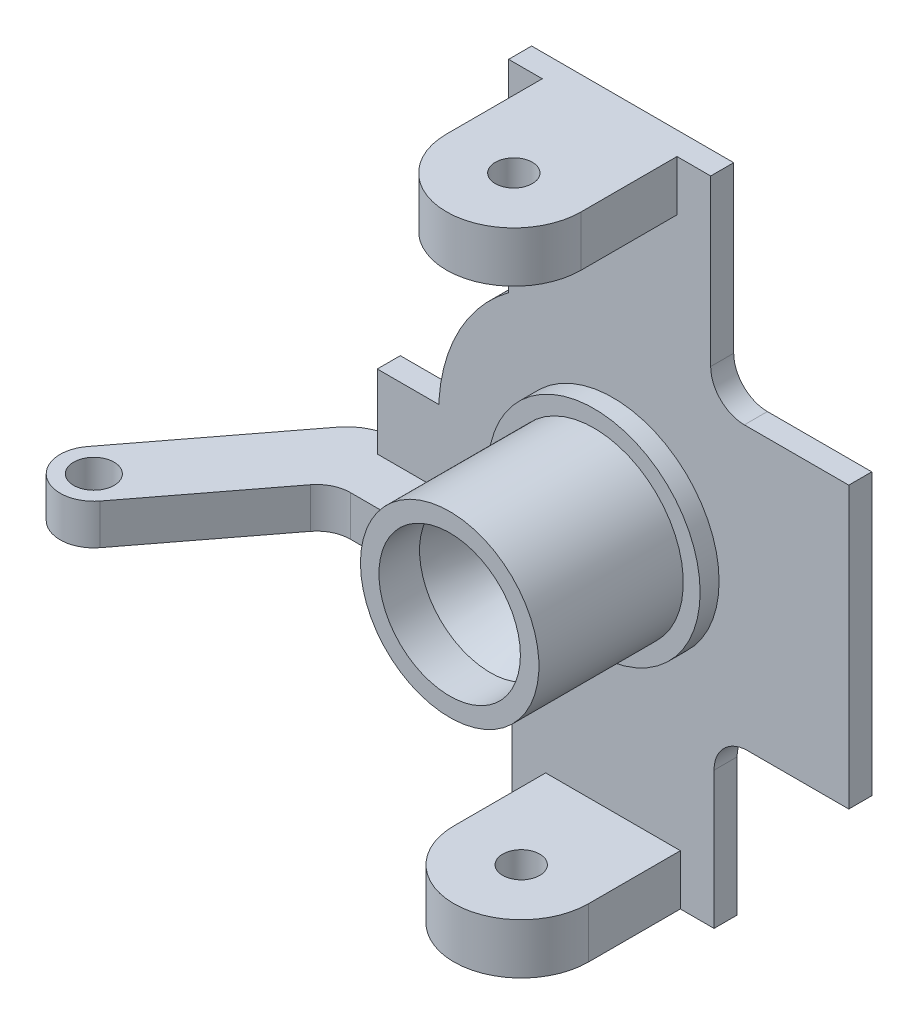
SolidWorks part; units mm, degrees
ref_plane "정면" through (0, 0, 0) normal (0, 0, 1) x (1, 0, 0)
ref_plane "윗면" through (0, 0, 0) normal (0, 1, 0) x (1, 0, 0)
ref_plane "우측면" through (0, 0, 0) normal (1, 0, 0) x (0, 0, -1)
sketch "스케치1" plane through (0, 0, 0) normal (0, 0, 1) x (1, 0, 0)
  line L0 (-34.9988, -181.1811) -> (-34.9988, -140.4811)
  line L1 (-95.9988, 11.8189) -> (-35.9988, 11.8189)
  line L2 (-134.9988, -87.3111) -> (-134.9988, -121.1811)
  line L3 (-94.9988, -181.1811) -> (-34.9988, -181.1811)
  line L4 (5.0012, -47.1811) -> (5.0012, -130.4811)
  line L5 (-24.9988, -130.4811) -> (5.0012, -130.4811)
  line L6 (-35.9988, 11.8189) -> (-35.9988, -37.1811)
  line L7 (-25.9988, -47.1811) -> (5.0012, -47.1811)
  line L8 (-134.9988, -121.1811) -> (-104.9988, -121.1811)
  line L9 (-94.9988, -131.1811) -> (-94.9988, -181.1811)
  line L11 (-95.9988, -48.1811) -> (-95.9988, 11.8189)
  line L12 (-134.9988, -87.3111) -> (-116.6823, -87.3111)
  line L13 (-116.6823, -87.3111) -> (-116.6823, -86.2066)
  arc A0 (-95.9988, -48.1811) -> (-116.6823, -86.2066) centre (-64.9988, -89.6811) ccw
  arc A1 (-35.9988, -37.1811) -> (-25.9988, -47.1811) centre (-25.9988, -37.1811) ccw
  arc A2 (-24.9988, -130.4811) -> (-34.9988, -140.4811) centre (-24.9988, -140.4811) ccw
  arc A3 (-94.9988, -131.1811) -> (-104.9988, -121.1811) centre (-104.9988, -131.1811) ccw
  point P17 (-35.9988, -47.1811)
  point P20 (-34.9988, -130.4811)
  point P23 (-94.9988, -121.1811)
  dimension "D8" = 10
  dimension "D10" = 70
  dimension "D1" = 60
  dimension "D2" = 193
  dimension "D3" = 40
  dimension "D4" = 50.7
  dimension "D5" = 59
  dimension "D6" = 41
  dimension "D7" = 40
  dimension "D9" = 91.5
  dimension "D11" = 60
  dimension "D12" = 60
  dimension "D13" = 33.87
  dimension "D14" = 60
extrude "보스-돌출1" add sketch "스케치1" along normal blind 6.84
sketch "스케치2" plane through (0, -121.1811, 0) normal (0, -1, 0) x (1, 0, 0)
  line L0 (-114.9988, 0) -> (-114.9988, 15.74)
  line L1 (-134.9988, 0) -> (-104.9988, 0) construction
  line L2 (-119.9988, 20.74) -> (-129.0934, 20.74)
  line L3 (-137.0434, 24.6739) -> (-164.0488, 60.0661)
  line L7 (-179.9488, 47.9339) -> (-147.8762, 5.9008)
  line L8 (-135.9512, 0) -> (-114.9988, 0)
  line L10 (-179.9488, 47.9339) -> (-164.0488, 60.0661)
  arc A0 (-119.9988, 20.74) -> (-114.9988, 15.74) centre (-119.9988, 15.74) cw
  arc A1 (-147.8762, 5.9008) -> (-135.9512, 0) centre (-135.9512, 15) ccw
  arc A2 (-137.0434, 24.6739) -> (-129.0934, 20.74) centre (-129.0934, 30.74) ccw
  arc A3 (-179.9488, 47.9339) -> (-164.0488, 60.0661) centre (-171.9988, 54) cw
  point P5 (0, 0)
  point P7 (-171.9988, 54)
  point P19 (0, 0)
  dimension "D1" = 5
  dimension "D2" = 15
  dimension "D3" = 10
  dimension "D7" = 54
  dimension "D4" = 20
  dimension "D5" = 20.74
  dimension "D8" = 57
extrude "보스-돌출2" add sketch "스케치2" against normal blind 12 contours L7 A1 L8 L0 A0 L2 A2 L3 A3
sketch "스케치3" plane through (0, 0, 6.84) normal (0, 0, 1) x (1, 0, 0)
  line L0 (-134.9988, -87.3111) -> (-134.9988, -109.1811) construction
  line L1 (-94.9988, -181.1811) -> (-34.9988, -181.1811) construction
  circle A0 centre (-64.9988, -91.1811) radius 26.5
  point P6 (-287.7561, 16.8097)
  dimension "D3" = 53
  dimension "D1" = 70
  dimension "D2" = 90
extrude "보스-돌출3" add sketch "스케치3" along normal blind 48.5
sketch "스케치4" plane through (0, 0, 6.84) normal (0, 0, 1) x (1, 0, 0)
  circle A0 centre (-64.9988, -91.1811) radius 31.5
  dimension "D1" = 63
extrude "보스-돌출4" add sketch "스케치4" along normal blind 5.63
sketch "스케치5" plane through (0, 0, 55.34) normal (0, 0, 1) x (1, 0, 0)
  circle A0 centre (-64.9988, -91.1811) radius 21
  dimension "D1" = 42
extrude "컷-돌출1" cut sketch "스케치5" against normal blind 9.13
sketch "스케치6" plane through (0, 0, 46.21) normal (0, 0, 1) x (1, 0, 0)
  circle A0 centre (-64.9988, -91.1811) radius 21
extrude "컷-돌출2" cut sketch "스케치6" against normal blind 2.92
ref_plane "평면1" through (0, 0, 28.29) normal (0, 0, 1) x (1, 0, 0)
sketch "스케치7" plane through (0, 0, 28.29) normal (0, 0, 1) x (1, 0, 0)
  circle A0 centre (-64.9988, -91.1811) radius 16
  dimension "D1" = 32
loft "컷-로프트1" cut profiles "스케치7" section "스케치7" section edge at (-43.9988, -91.1811, 43.29)
ref_plane "평면2" through (0, 0, 15) normal (0, 0, -1) x (-1, 0, 0)
ref_plane "평면3" through (0, 0, 15) normal (0, 0, -1) x (-1, 0, 0)
sketch "스케치8" plane through (0, 0, 15) normal (0, 0, -1) x (-1, 0, 0)
  circle A0 centre (64.9988, -91.1811) radius 16
  dimension "D1" = 32
sketch "스케치9" plane through (0, 0, 0) normal (0, 0, -1) x (-1, 0, 0)
  circle A0 centre (64.9988, -91.1811) radius 21
  dimension "D1" = 42
loft "컷-로프트3" cut profiles "스케치9", "스케치8"
sketch "스케치10" plane through (0, 0, 15) normal (0, 0, -1) x (-1, 0, 0)
  circle A0 centre (64.9988, -91.1811) radius 17
  dimension "D1" = 34
extrude "컷-돌출3" cut sketch "스케치10" against normal blind 13.29
sketch "스케치11" plane through (0, -109.1811, 0) normal (0, 1, 0) x (1, 0, 0)
  circle A0 centre (-171.9988, -54) radius 6
  dimension "D1" = 12
extrude "컷-돌출4" cut sketch "스케치11" against normal blind 42.92
sketch "스케치12" plane through (0, -181.1811, 0) normal (0, -1, 0) x (1, 0, 0)
  line L0 (-84.9988, 6.84) -> (-84.9988, 34.0914)
  line L1 (-94.9988, 6.84) -> (-34.9988, 6.84) construction
  line L3 (-44.9988, 34.0914) -> (-44.9988, 6.84)
  line L4 (-44.9988, 6.84) -> (-84.9988, 6.84)
  line L5 (-94.9988, 6.84) -> (-94.9988, 0) construction
  arc A0 (-44.9988, 34.0914) -> (-84.9988, 34.0914) centre (-64.9988, 34.0914) ccw
  dimension "D1" = 40
  dimension "D2" = 10
extrude "보스-돌출5" add sketch "스케치12" against normal blind 15
sketch "스케치13" plane through (0, -181.1811, 0) normal (0, -1, 0) x (1, 0, 0)
  circle A0 centre (-64.9988, 34.0914) radius 5.5
  dimension "D1" = 11
extrude "컷-돌출5" cut sketch "스케치13" against normal blind 15
sketch "스케치15" plane through (0, 11.8189, 0) normal (0, 1, 0) x (1, 0, 0)
  line L0 (-85.9988, -6.84) -> (-85.9988, -35.2864)
  line L1 (-35.9988, -6.84) -> (-95.9988, -6.84) construction
  line L3 (-45.9988, -35.2864) -> (-45.9988, -6.84)
  line L4 (-45.9988, -6.84) -> (-85.9988, -6.84)
  line L5 (-95.9988, -6.84) -> (-95.9988, 0) construction
  arc A0 (-85.9988, -35.2864) -> (-45.9988, -35.2864) centre (-65.9988, -35.2864) ccw
  point P7 (-65.9988, -6.84)
  dimension "D1" = 40
  dimension "D2" = 30
extrude "보스-돌출6" add sketch "스케치15" against normal blind 15
sketch "스케치16" plane through (0, 11.8189, 0) normal (0, 1, 0) x (1, 0, 0)
  circle A0 centre (-65.9988, -35.2864) radius 5.5
  dimension "D1" = 11
extrude "컷-돌출6" cut sketch "스케치16" against normal blind 15
